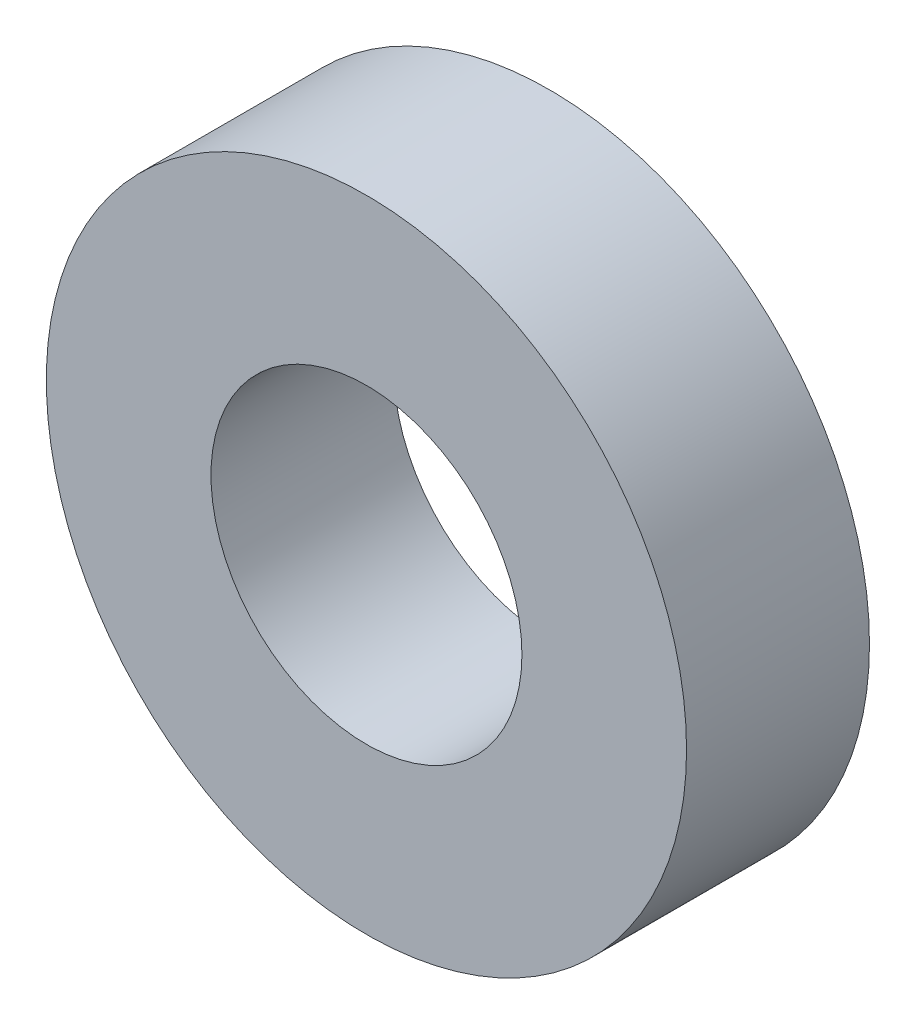
SolidWorks part; units mm, degrees
ref_plane "Спереди" through (0, 0, 0) normal (0, 0, 1) x (1, 0, 0)
ref_plane "Сверху" through (0, 0, 0) normal (0, 1, 0) x (1, 0, 0)
ref_plane "Справа" through (0, 0, 0) normal (1, 0, 0) x (0, 0, -1)
sketch "Эскиз1" plane through (0, 0, 0) normal (0, 0, 1) x (1, 0, 0)
  circle A0 centre (0, 0) radius 17.5
  circle A1 centre (0, 0) radius 8.5
extrude "Rear_bearing" add sketch "Эскиз1" along normal blind 10 from offset 42
